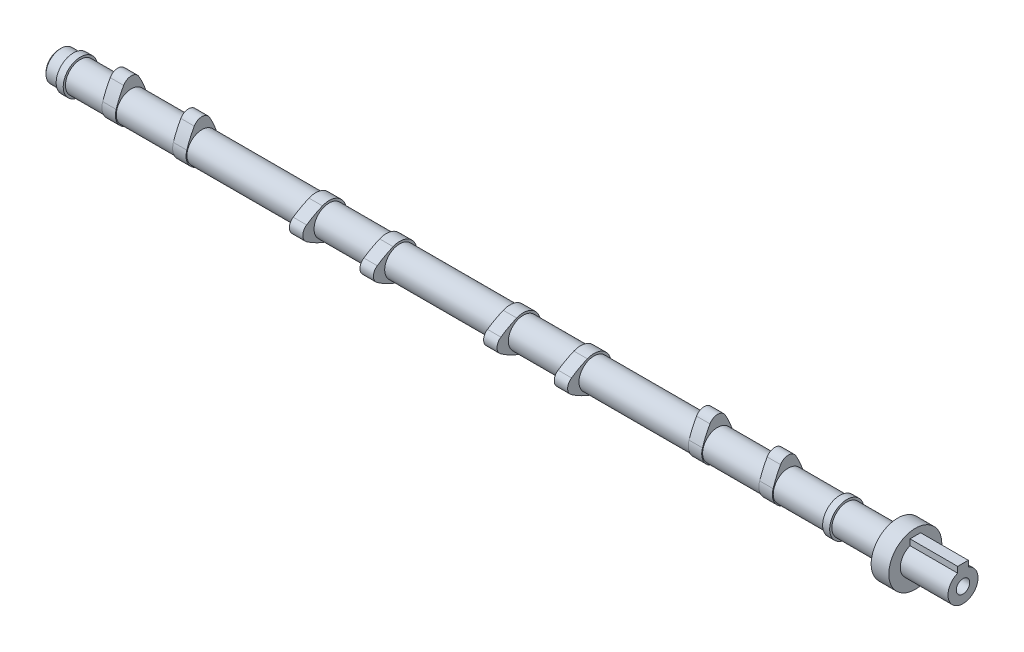
SolidWorks part; units mm, degrees
ref_plane "Alzado" through (0, 0, 0) normal (0, 0, 1) x (1, 0, 0)
ref_plane "Planta" through (0, 0, 0) normal (0, 1, 0) x (1, 0, 0)
ref_plane "Vista lateral" through (0, 0, 0) normal (1, 0, 0) x (0, 0, -1)
sketch "Croquis1" plane through (0, 0, 0) normal (0, 0, 1) x (1, 0, 0)
  line L0 (0, 0) -> (580, 0)
  line L1 (0, 0) -> (0, 8.5)
  line L2 (0, 8.5) -> (580, 8.5) construction
  line L3 (580, 8.5) -> (580, 0)
  line L4 (0, 8.5) -> (580, 8.5)
  dimension "D1" = 580
  dimension "D2" = 17
revolve "Revolución1" add sketch "Croquis1" angle 360 about L2
sketch "Croquis2" plane through (580, 0, 0) normal (1, 0, 0) x (0, 0, -1)
  circle A0 centre (0, 8.5) radius 31.2943
  circle A1 centre (0, 8.5) radius 8.5 construction
sketch "Croquis3" plane through (580, 0, 0) normal (1, 0, 0) x (0, 0, -1)
sketch "Croquis4" plane through (580, 0, 0) normal (1, 0, 0) x (0, 0, -1)
  circle A0 centre (0, 8.5) radius 9.75
  dimension "D1" = 19.5
extrude "Saliente-Extruir1" add sketch "Croquis4" against normal blind 4
pattern_linear "MatrizL1" count 2 spacing 442 along (-1, 0, 0) of "Saliente-Extruir1"
ref_plane "Plano1" through (171, 0, 0) normal (1, 0, 0) x (0, 0, -1)
sketch "Croquis5" plane through (171, 0, 0) normal (1, 0, 0) x (0, 0, -1)
  line L0 (0, 8.5) -> (0, 23.4) construction
  arc A1 (-8.5769, 11.2272) -> (8.5769, 11.2272) centre (0, 8.5) ccw
  arc A2 (4.3414, 20.8804) -> (-4.3414, 20.8804) centre (0, 18.4) ccw
  arc A3 (-4.3414, 20.8804) -> (-8.5769, 11.2272) centre (39.0724, -3.9237) ccw
  arc A4 (4.3414, 20.8804) -> (8.5769, 11.2272) centre (-39.0724, -3.9237) cw
  point P6 (0, 23.4)
  dimension "D1" = 14.9
  dimension "D2" = 10
  dimension "D3" = 18
  dimension "D4" = 100
extrude "Saliente-Extruir3" add sketch "Croquis5" along normal blind 3.8 and the other way blind 3.8
pattern_linear "MatrizL2" count 2 spacing 40 along (1, 0, 0) of "Saliente-Extruir3"
pattern_linear "MatrizL3" count 2 spacing 332 along (1, 0, 0) of "MatrizL2", "Saliente-Extruir3"
ref_plane "Plano2" through (281, 0, 0) normal (1, 0, 0) x (0, 0, -1)
sketch "Croquis6" plane through (281, 0, 0) normal (1, 0, 0) x (0, 0, -1)
  line L0 (0, 23.4) -> (0, 8.5) construction
  line L1 (0, 8.5) -> (-14.9, 8.5) construction
  arc A0 (4.3414, 20.8804) -> (-4.3414, 20.8804) centre (0, 18.4) ccw construction
  arc A1 (-12.7224, 12.6272) -> (-12.7224, 4.3728) centre (-9.9, 8.5) ccw
  circle A2 centre (0, 8.5) radius 8.5 construction
  circle A3 centre (0, 8.5) radius 9.75 construction
  arc A4 (-3.755, -0.4979) -> (-3.755, 17.4979) centre (0, 8.5) ccw
  arc A5 (-12.7224, 4.3728) -> (-3.755, -0.4979) centre (15.5014, 45.6452) ccw
  arc A6 (-3.755, 17.4979) -> (-12.7224, 12.6272) centre (15.5014, -28.6452) ccw
  circle A7 centre (0, 8.5) radius 8.5
  dimension "D1" = 10
  dimension "D2" = 50
  dimension "D3" = 100
extrude "Saliente-Extruir4" add sketch "Croquis6" against normal blind 3.8 and the other way blind 3.8
pattern_linear "MatrizL4" count 2 spacing 40 along (1, 0, 0) of "Saliente-Extruir4"
pattern_linear "MatrizL5" count 2 spacing 110 along (1, 0, 0) of "MatrizL4", "Saliente-Extruir4"
mirror "Simetría1" about plane through (0, 0, 0) normal (-1, 0, 0) of bodies 110
delete or keep bodies "Sólido-Eliminar/Conservar 1" type delete bodies bodies 110
sketch "Croquis7" plane through (-580, 0, 0) normal (-1, 0, 0) x (0, 0, 1)
  circle A1 centre (0, 8.5) radius 9.75
  circle A2 centre (0, 8.5) radius 9.75
  dimension "D1" = 0
extrude "Cortar-Extruir1" cut sketch "Croquis7" against normal blind 12
sketch "Croquis8" plane through (-568, 0, 0) normal (-1, 0, 0) x (0, 0, 1)
  circle A0 centre (0, 8.5) radius 9.75
  dimension "D1" = 19.5
extrude "Saliente-Extruir5" add sketch "Croquis8" along normal blind 4
sketch "Croquis9" plane through (-572, 0, 0) normal (-1, 0, 0) x (0, 0, 1)
  circle A0 centre (0, 8.5) radius 8.5
  dimension "D1" = 17
extrude "Saliente-Extruir6" add sketch "Croquis9" along normal blind 8
chamfer "Chaflán1" distance 1 angle 45 1 edges at (-580, 8.5, 8.5)
ref_plane "Plano3" through (-100.25, 0, 0) normal (1, 0, 0) x (0, 0, -1)
sketch "Croquis10" plane through (-100.25, 0, 0) normal (1, 0, 0) x (0, 0, -1)
  circle A0 centre (0, 8.5) radius 15
  dimension "D1" = 30
extrude "Saliente-Extruir7" add sketch "Croquis10" along normal blind 5 and the other way blind 5
sketch "Croquis11" plane through (-95.25, 0, 0) normal (1, 0, 0) x (0, 0, -1)
  line L0 (0, 0) -> (0, 16.453) construction
  line L1 (-3, 19.803) -> (3, 19.803)
  line L2 (-3, 19.803) -> (-3, 16.453)
  line L3 (-3, 16.453) -> (3, 16.453)
  line L4 (3, 19.803) -> (3, 16.453)
  circle A0 centre (0, 8.5) radius 8.5 construction
  arc A1 (3, 16.453) -> (-3, 16.453) centre (0, 8.5) ccw construction
  dimension "D1" = 3.35
  dimension "D2" = 6
extrude "Saliente-Extruir8" add sketch "Croquis11" along normal blind 40
ref_plane "Plano4" through (-68.25, 0, 0) normal (1, 0, 0) x (0, 0, -1)
sketch "Croquis12" plane through (0, 0, 0) normal (1, 0, 0) x (0, 0, -1)
  circle A0 centre (0, 8.5) radius 42.0659
extrude "Cortar-Extruir2" cut sketch "Croquis12" against normal up to surface (68.25 mm away)
sketch "Croquis13" plane through (-68.25, 0, 0) normal (1, 0, 0) x (0, 0, -1)
  point P0 (0, 8.5)
hole_wizard "Taladro de margen para M71" positions "Croquis3D1" profile "Croquis14" hole size "M7" standard "Ansi Metric"
sketch3d "Croquis3D1"
  point P0 (-68.25, 8.5, 0)
sketch "Croquis14" plane through (-68.25, 8.5, 0) normal (0, 1, 0) x (0, 0, -1)
  line L0 (0, 0) -> (0, 32.2833)
  line L1 (0, 32.2833) -> (3.8, 30)
  line L2 (3.8, 30) -> (3.8, 0)
  line L5 (3.8, 0) -> (0, 0)
  line L10 (0, 32.2833) -> (-3.8, 30) construction
  line L11 (0, -6.35) -> (0, 107.95) construction
  dimension "Diámetro de taladro" = 7.6
  dimension "Profundidad de taladro" = 30
  dimension "Ángulo de perforador" = 118
